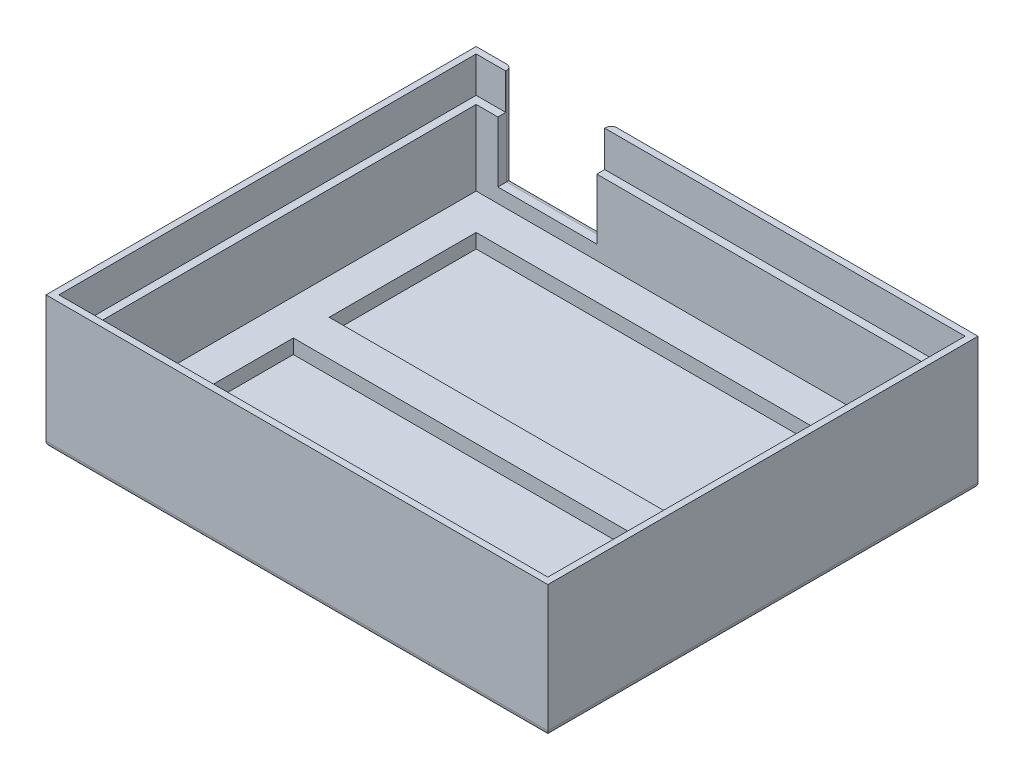
SolidWorks part; units mm, degrees
ref_plane "Front Plane" through (0, 0, 0) normal (0, 0, 1) x (1, 0, 0)
ref_plane "Top Plane" through (0, 0, 0) normal (0, 1, 0) x (1, 0, 0)
ref_plane "Right Plane" through (0, 0, 0) normal (1, 0, 0) x (0, 0, -1)
sketch "Sketch1" plane through (0, 0, 0) normal (0, 1, 0) x (1, 0, 0)
  line L1 (-22.5564, 15.5545) -> (47.4436, 15.5545)
  line L2 (-22.5564, 15.5545) -> (-22.5564, -44.4455)
  line L3 (-22.5564, -44.4455) -> (47.4436, -44.4455)
  line L4 (47.4436, 15.5545) -> (47.4436, -44.4455)
  dimension "D1" = 70
  dimension "D2" = 60
  dimension "D3" = 47.4436
  dimension "D4" = 15.5545
extrude "Boss-Extrude1" add sketch "Sketch1" along normal blind 1
sketch "Sketch2" plane through (0, 1, 0) normal (0, 1, 0) x (1, 0, 0)
  line L11 (-22.5564, 15.5545) -> (47.4436, 15.5545)
  line L12 (-22.5564, 15.5545) -> (-22.5564, -44.4455)
  line L13 (-22.5564, -44.4455) -> (47.4436, -44.4455)
  line L14 (-20.5564, 13.5545) -> (-20.5564, -42.4455)
  line L15 (-20.5564, -42.4455) -> (45.4436, -42.4455)
  line L16 (45.4436, -42.4455) -> (45.4436, 13.5545)
  line L17 (45.4436, 13.5545) -> (-20.5564, 13.5545)
  line L18 (-20.5564, 13.5545) -> (-20.5564, -42.4455)
  line L19 (-20.5564, -42.4455) -> (45.4436, -42.4455)
  line L20 (45.4436, -42.4455) -> (45.4436, 13.5545)
  line L21 (45.4436, 13.5545) -> (-20.5564, 13.5545)
  line L22 (47.4436, 15.5545) -> (47.4436, -44.4455)
  dimension "D1" = 2
extrude "Boss-Extrude2" add sketch "Sketch2" along normal blind 17.46
sketch "Sketch3" plane through (0, 1, 0) normal (0, 1, 0) x (1, 0, 0)
  line L18 (-15.5564, 8.5545) -> (-15.5564, -37.4455)
  line L19 (-20.5564, 13.5545) -> (45.4436, 13.5545)
  line L22 (-20.5564, 13.5545) -> (-20.5564, -42.4455)
  line L23 (-20.5564, -42.4455) -> (45.4436, -42.4455)
  line L24 (45.4436, 13.5545) -> (45.4436, -42.4455)
  line L25 (-15.5564, -37.4455) -> (40.4436, -37.4455)
  line L26 (40.4436, 8.5545) -> (40.4436, -37.4455)
  line L27 (-15.5564, 8.5545) -> (40.4436, 8.5545)
  dimension "D1" = 5
extrude "Boss-Extrude4" add sketch "Sketch3" along normal blind 2
sketch "Sketch4" plane through (0, 0, -15.5545) normal (0, 0, -1) x (-1, 0, 0)
  line L0 (3.7224, 18.4646) -> (3.7224, 6.206)
  line L1 (4.0224, 18.1646) -> (17.2304, 18.1646)
  line L2 (4.0224, 18.1646) -> (4.0224, 6.506)
  line L3 (4.0224, 6.506) -> (17.2304, 6.506)
  line L4 (17.2304, 18.1646) -> (17.2304, 6.506)
  line L6 (17.5304, 18.4646) -> (17.5304, 6.206)
  line L7 (3.7224, 18.4646) -> (17.5304, 18.4646)
  line L8 (3.7224, 6.206) -> (17.5304, 6.206) construction
  line L10 (3.7224, 6.206) -> (3.7224, 5.006)
  line L11 (3.7224, 5.006) -> (17.5304, 5.006)
  line L12 (17.5304, 5.006) -> (17.5304, 6.206)
  dimension "D2" = 1.5
  dimension "D1" = 0.3
extrude "Cut-Extrude2" cut sketch "Sketch4" against normal blind 10
sketch "Sketch8" plane through (0, 1, 0) normal (0, 1, 0) x (1, 0, 0)
  line L0 (-15.5564, 8.5545) -> (-15.5564, -37.4455) construction
  line L1 (-15.5564, -11.9455) -> (40.4436, -11.9455)
  line L2 (-15.5564, -11.9455) -> (-15.5564, -16.9455)
  line L3 (-15.5564, -16.9455) -> (40.4436, -16.9455)
  line L4 (40.4436, -11.9455) -> (40.4436, -16.9455)
  line L5 (40.4436, -37.4455) -> (40.4436, 8.5545) construction
  line L6 (40.4436, -16.9455) -> (-15.5564, -11.9455) construction
  line L7 (-15.5564, -16.9455) -> (40.4436, -11.9455) construction
  line L8 (-15.5564, 8.5545) -> (40.4436, -37.4455) construction
  line L9 (40.4436, -37.4455) -> (-15.5564, -37.4455) construction
  line L10 (-15.5564, -37.4455) -> (40.4436, 8.5545) construction
  point P9 (12.4436, -14.4455)
  point P14 (12.4436, -14.4455)
  dimension "D1" = 5
extrude "Boss-Extrude5" add sketch "Sketch8" along normal blind 2
sketch "Sketch9" plane through (0, 3, 0) normal (0, 1, 0) x (1, 0, 0)
  line L0 (45.4436, -42.4455) -> (45.4436, 13.5545) construction
  line L1 (40.4436, -16.9455) -> (45.4436, -16.9455)
  line L2 (40.4436, -16.9455) -> (40.4436, -37.4455)
  line L3 (40.4436, -37.4455) -> (45.4436, -37.4455)
  line L4 (45.4436, -16.9455) -> (45.4436, -37.4455)
  line L5 (-15.5564, -37.4455) -> (40.4436, -37.4455) construction
extrude "Cut-Extrude3" cut sketch "Sketch9" against normal blind 2
sketch "Sketch13" plane through (0, 18.46, 0) normal (0, 1, 0) x (1, 0, 0)
  line L0 (46.5436, -43.5455) -> (-21.6564, -43.5455)
  line L1 (45.4436, -42.4455) -> (-20.5564, -42.4455)
  line L2 (45.4436, -42.4455) -> (45.4436, 13.5545)
  line L3 (45.4436, 13.5545) -> (-20.5564, 13.5545)
  line L4 (-20.5564, -42.4455) -> (-20.5564, 13.5545)
  line L5 (-21.6564, -43.5455) -> (-21.6564, 14.6545)
  line L6 (46.5436, 14.6545) -> (-21.6564, 14.6545)
  line L7 (46.5436, -43.5455) -> (46.5436, 14.6545)
  dimension "D1" = 1.1
extrude "Cut-Extrude6" cut sketch "Sketch13" against normal blind 5
fillet "Fillet1" radius 0.8 4 edges at (12.4436, 0, 44.4455) (47.4436, 0, 14.4455) (12.4436, 0, -15.5545) (-22.5564, 0, 14.4455)
fillet "Fillet2" radius 0.8 3 edges at (-17.5304, 11.733, -15.5545) (-3.7224, 11.733, -15.5545) (-10.6264, 5.006, -15.5545)
equation "\"assembly_offset\"= 0.3mm"
equation "\"case_thickness\"= 1mm"
equation "\"case_length\"= 60mm"
equation "\"case_width\"= 70mm"
equation "\"case_height\"= 17.16 + \"assembly_offset\""
equation "\"D1@Boss-Extrude1\"=\"case_thickness\""
equation "\"D1@Sketch2\"=\"case_thickness\"*2"
equation "\"D1@Boss-Extrude2\"=\"case_height\""
equation "\"D1@Sketch1\"=\"case_width\""
equation "\"D2@Sketch1\"=\"case_length\""
equation "\"pcb_offset\"= 2mm"
equation "\"D1@Boss-Extrude4\"=\"pcb_offset\""
equation "\"D1@Sketch4\"=\"assembly_offset\""
equation "\"usb_offset\"= 5.5mm"
equation "\"D1@Boss-Extrude5\"=\"pcb_offset\""
equation "\"pcb_offset_thickness\"= 5mm"
equation "\"D1@Sketch8\"=\"pcb_offset_thickness\""
equation "\"D1@Sketch3\"=\"pcb_offset_thickness\""
equation "\"D1@Cut-Extrude3\"=\"pcb_offset\""
equation "\"D1@Sketch13\"=\"case_thickness\"+\"connect_wall_assembly_offset\""
equation "\"case_connect_wall\"= 5mm"
equation "\"D1@Cut-Extrude6\"=\"case_connect_wall\""
equation "\"connect_wall_assembly_offset\"= 0.1mm"
equation "\"fillet_topbottom\"= 0.8mm"
equation "\"D1@Fillet1\"=\"fillet_topbottom\""
equation "\"D1@Fillet2\"=\"fillet_topbottom\""
